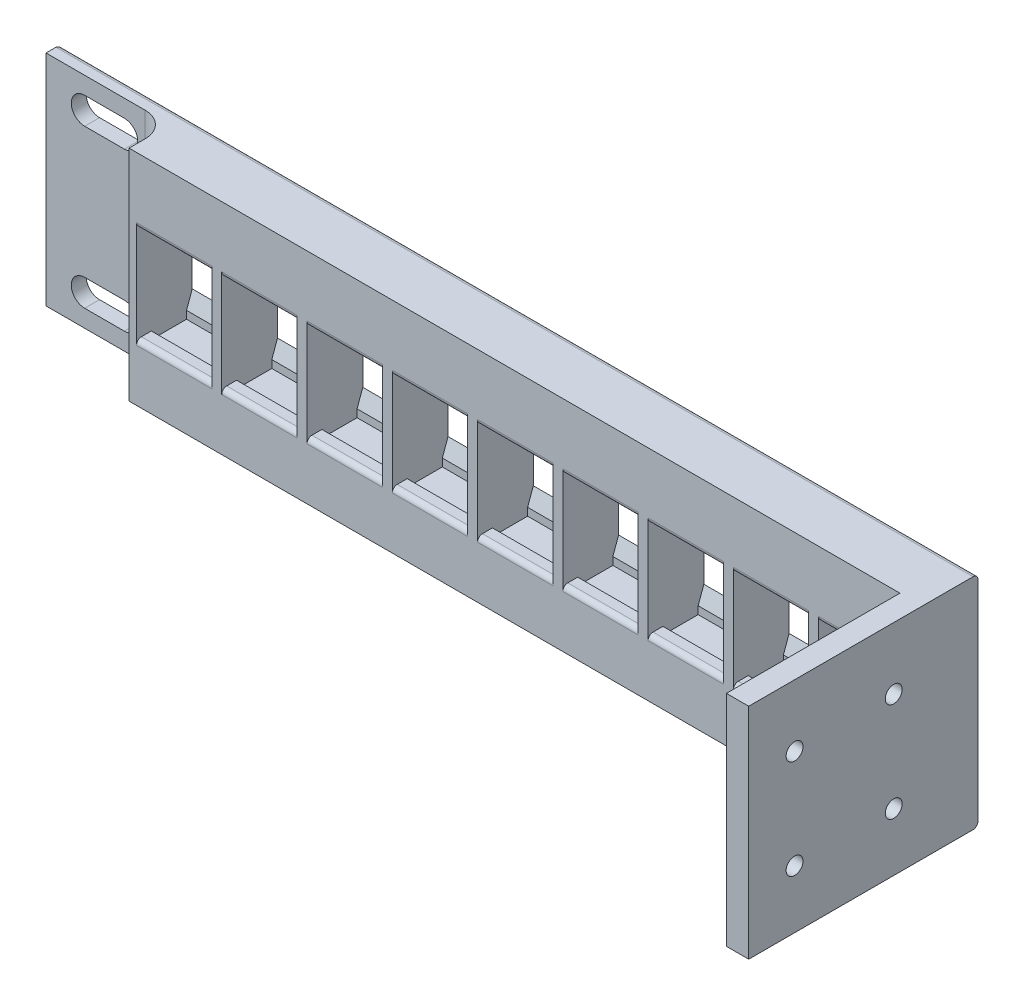
SolidWorks part; units mm, degrees
ref_plane "Front Plane" through (0, 0, 0) normal (0, 0, 1) x (1, 0, 0)
ref_plane "Top Plane" through (0, 0, 0) normal (0, 1, 0) x (1, 0, 0)
ref_plane "Right Plane" through (0, 0, 0) normal (1, 0, 0) x (0, 0, -1)
sketch "Sketch1" plane through (0, 0, 0) normal (0, 0, 1) x (1, 0, 0)
  line L1 (-92.5, 22.1) -> (92.5, 22.1)
  line L2 (-92.5, 22.1) -> (-92.5, -22.1)
  line L3 (-92.5, -22.1) -> (92.5, -22.1)
  line L4 (92.5, 22.1) -> (92.5, -22.1)
  line L5 (-92.5, 22.1) -> (92.5, -22.1) construction
  line L6 (-92.5, -22.1) -> (92.5, 22.1) construction
  point P0 (0, 0)
  dimension "D1" = 185
  dimension "D2" = 44.2
extrude "Boss-Extrude1" add sketch "Sketch1" along normal blind 11.25
sketch "Sketch2" plane through (0, 0, 11.25) normal (0, 0, 1) x (1, 0, 0)
  line L0 (-92.5, -22.1) -> (92.5, -22.1) construction
  line L1 (-92.5, 22.1) -> (-67.5, 22.1)
  line L2 (-92.5, 22.1) -> (-92.5, -22.1)
  line L3 (-92.5, -22.1) -> (-67.5, -22.1)
  line L4 (-67.5, 22.1) -> (-67.5, -22.1)
  dimension "D1" = 25
extrude "Cut-Extrude1" cut sketch "Sketch2" against normal offset from surface (8.25 mm away) 3 up to face at (0, 0, 0)
fillet "Fillet1" radius 5 1 edges at (-67.5, 0, 3)
ref_plane "Plane1" through (-66, 0, 0) normal (-1, 0, 0) x (0, 0, 1)
sketch "Sketch3" plane through (-66, 0, 0) normal (-1, 0, 0) x (0, 0, 1)
  line L0 (0, 8.85) -> (1.15, 8.85)
  line L1 (0, 22.1) -> (0, -22.1) construction
  line L2 (1.15, 8.85) -> (1.15, 10.35)
  line L3 (1.15, 10.35) -> (8.25, 10.35)
  line L4 (8.25, 10.35) -> (8.25, 8.85)
  line L5 (8.25, 8.85) -> (11.25, 8.85)
  line L6 (11.25, 8.85) -> (11.25, -10.6)
  line L7 (11.25, -10.6) -> (8.25, -10.6)
  line L8 (8.25, -10.6) -> (8.25, -12.1)
  line L9 (8.25, -12.1) -> (1.15, -12.1)
  line L10 (1.15, -12.1) -> (1.15, -10.5457)
  line L11 (1.15, -10.5457) -> (0, -7.36)
  line L12 (0, -7.36) -> (0, 8.85)
  line L13 (3, -22.1) -> (0, -22.1) construction
  dimension "D1" = 1.15
  dimension "D2" = 1.5
  dimension "D3" = 7.1
  dimension "D4" = 3
  dimension "D5" = 1.5
  dimension "D6" = 19.45
  dimension "D7" = 3
  dimension "D8" = 1.5
  dimension "D9" = 7.1
  dimension "D10" = 16.21
  dimension "D11" = 10
extrude "Cut-Extrude2" cut sketch "Sketch3" against normal blind 15.2
pattern_linear "LPattern1" count 9 spacing 17.2 along (1, 0, 0) of "Cut-Extrude2"
sketch "Sketch4" plane through (0, 0, 11.25) normal (0, 0, 1) x (1, 0, 0)
  line L0 (-67.5, -22.1) -> (92.5, -22.1) construction
  line L1 (92.5, 22.1) -> (88, 22.1)
  line L2 (92.5, 22.1) -> (92.5, -22.1)
  line L3 (92.5, -22.1) -> (88, -22.1)
  line L4 (88, 22.1) -> (88, -22.1)
  dimension "D1" = 4.5
extrude "Boss-Extrude2" add sketch "Sketch4" along normal blind 35
sketch "Sketch9" plane through (86.8, 0, 0) normal (-1, 0, 0) x (0, 0, 1)
  line L0 (0, -22.1) -> (0, 22.1) construction
  line L1 (46.25, 22.1) -> (11.25, 22.1) construction
  point P0 (17, 9.6)
  point P2 (37, 9.6)
  point P4 (17, -10.4)
  point P6 (37, -10.4)
  dimension "D1" = 17
  dimension "D2" = 20
  dimension "D3" = 20
  dimension "D4" = 12.5
hole_wizard "CBORE for M3 SHCS1" positions "Sketch9" profile "Sketch8" counterbore size "M3" standard "ANSI Metric"
sketch "Sketch8" plane through (86.8, 9.6, 17) normal (0, 1, 0) x (0, 0, 1)
  line L0 (0, 0) -> (0, 11.1215)
  line L1 (0, 11.1215) -> (1.7, 10.1)
  line L2 (1.7, 10.1) -> (1.7, 3)
  line L3 (1.7, 3) -> (3.25, 3)
  line L4 (3.25, 3) -> (3.25, 0)
  line L5 (3.25, 0) -> (0, 0)
  line L10 (0, 11.1215) -> (-1.7, 10.1) construction
  line L11 (0, -6.35) -> (0, 107.95) construction
  dimension "Hole Dia." = 3.4
  dimension "Hole Depth" = 10.1
  dimension "C'Bore Dia." = 6.5
  dimension "C'Bore Depth" = 3
  dimension "Drill Angle" = 118
sketch "Sketch10" plane through (0, 0, 0) normal (0, 0, -1) x (-1, 0, 0)
  line L0 (76.7, 15.9) -> (84.7, 15.9) construction
  line L1 (76.7, 18.6) -> (84.7, 18.6)
  line L2 (76.7, 13.2) -> (84.7, 13.2)
  line L6 (76.7, -15.9) -> (84.7, -15.9) construction
  line L7 (76.7, -13.2) -> (84.7, -13.2)
  line L8 (76.7, -18.6) -> (84.7, -18.6)
  line L9 (67.5, -22.1) -> (67.5, 22.1) construction
  arc A0 (76.7, 18.6) -> (76.7, 13.2) centre (76.7, 15.9) ccw
  arc A1 (84.7, 13.2) -> (84.7, 18.6) centre (84.7, 15.9) ccw
  arc A2 (76.7, -13.2) -> (76.7, -18.6) centre (76.7, -15.9) ccw
  arc A3 (84.7, -18.6) -> (84.7, -13.2) centre (84.7, -15.9) ccw
  point P2 (80.7, 15.9)
  point P7 (74, 15.9)
  point P14 (80.7, -15.9)
  dimension "D3" = 6.5
  dimension "D1" = 5.4
  dimension "D2" = 8
  dimension "D4" = 15.9
  dimension "D6" = 15.9
  dimension "D5" = 2
extrude "Cut-Extrude3" cut sketch "Sketch10" against normal blind 35
fillet "Fillet2" radius 1 18 edges at (79.2, 8.85, 11.25) (79.2, -10.6, 11.25) (62, -10.6, 11.25) (62, 8.85, 11.25) (44.8, 8.85, 11.25) (44.8, -10.6, 11.25) (27.6, -10.6, 11.25) (27.6, 8.85, 11.25) (10.4, -10.6, 11.25) (10.4, 8.85, 11.25) (-6.8, 8.85, 11.25) (-6.8, -10.6, 11.25) (-24, -10.6, 11.25) (-24, 8.85, 11.25) (-41.2, 8.85, 11.25) (-41.2, -10.6, 11.25) (-58.4, -10.6, 11.25) (-58.4, 8.85, 11.25)
fillet "Fillet3" radius 1 3 edges at (-92.5, 0, 0) (0, -22.1, 0) (0, 22.1, 0)
